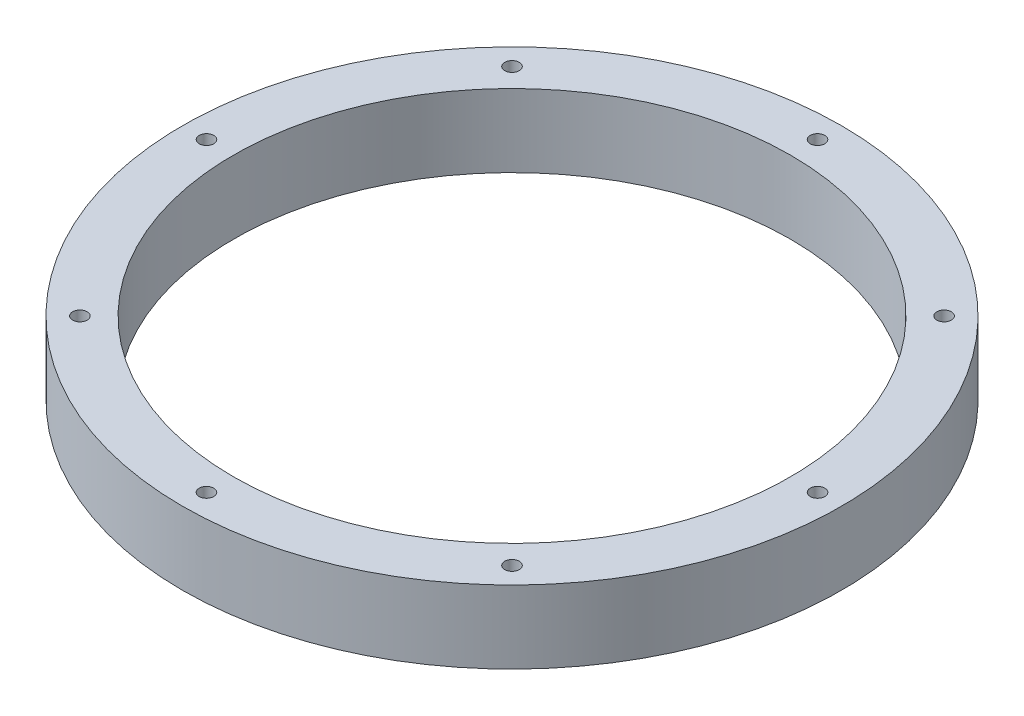
SolidWorks part; units mm, degrees
ref_plane "前视基准面" through (0, 0, 0) normal (0, 0, 1) x (1, 0, 0)
ref_plane "上视基准面" through (0, 0, 0) normal (0, 1, 0) x (1, 0, 0)
ref_plane "右视基准面" through (0, 0, 0) normal (1, 0, 0) x (0, 0, -1)
other "Configuration Table"
sketch "草图1" plane through (0, 0, 0) normal (0, 0, 1) x (1, 0, 0)
  line L0 (0, 0) -> (0, 30.9262) construction
  line L2 (76.5, 0) -> (90.5, 0)
  line L3 (76.5, 0) -> (76.5, 20)
  line L4 (76.5, 20) -> (90.5, 20)
  line L5 (90.5, 0) -> (90.5, 20)
  dimension "D1" = 90.5
  dimension "D2" = 14
  dimension "D3" = 20
revolve "旋转1" add sketch "草图1" angle 360 about L0
sketch "草图2" plane through (0, 20, 0) normal (0, 1, 0) x (1, 0, 0)
  circle A0 centre (0, 0) radius 83.9 construction
  circle A2 centre (-83.9, 0) radius 2
  circle A4 centre (-59.3263, 59.3263) radius 2
  circle A5 centre (0, 83.9) radius 2
  circle A6 centre (59.3263, 59.3263) radius 2
  circle A7 centre (83.9, 0) radius 2
  circle A8 centre (59.3263, -59.3263) radius 2
  circle A9 centre (0, -83.9) radius 2
  circle A10 centre (-59.3263, -59.3263) radius 2
  point P24 (0, 0)
  dimension "D1" = 167.8
  dimension "D2" = 4
  dimension "D3" = 8
extrude "切除-拉伸1" cut sketch "草图2" against normal through all
